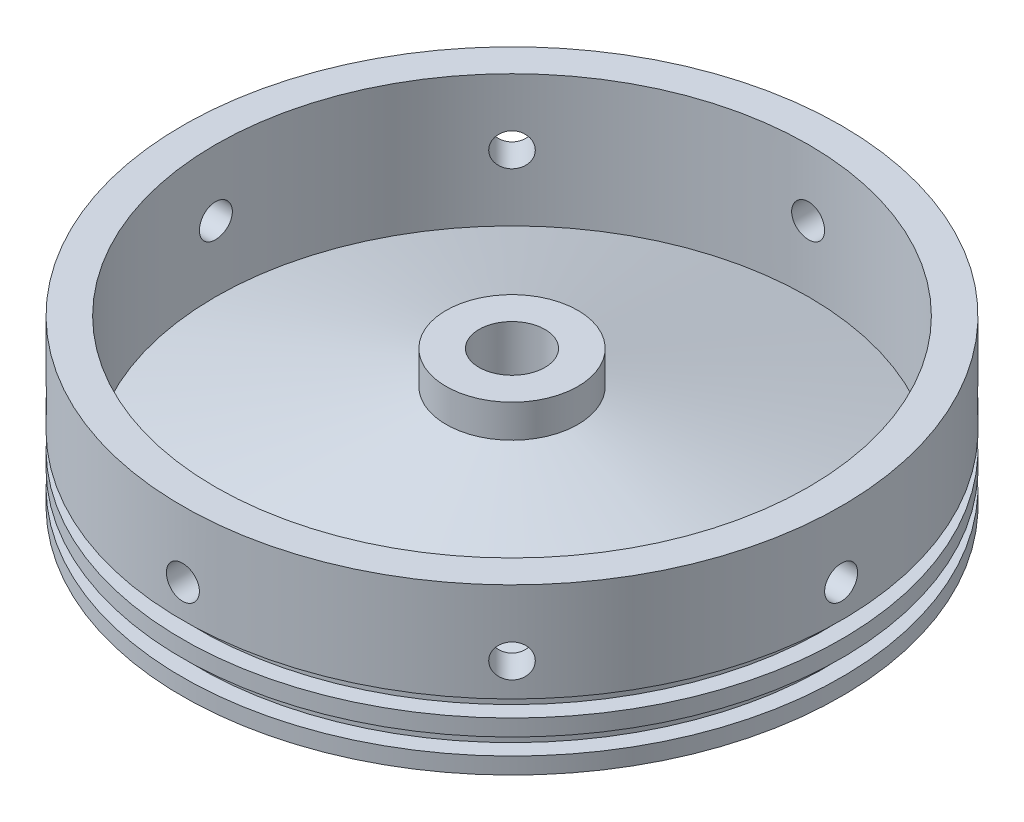
SolidWorks part; units mm, degrees
ref_plane "Front Plane" through (0, 0, 0) normal (0, 0, 1) x (1, 0, 0)
ref_plane "Top Plane" through (0, 0, 0) normal (0, 1, 0) x (1, 0, 0)
ref_plane "Right Plane" through (0, 0, 0) normal (1, 0, 0) x (0, 0, -1)
sketch "Sketch1" plane through (0, 0, 0) normal (0, 0, 1) x (1, 0, 0)
  line L2 (6.35, 32.6634) -> (6.35, 45.3634)
  line L11 (57.15, 50.8) -> (63.5, 50.8)
  line L13 (6.35, 45.3634) -> (12.7, 45.3634)
  line L14 (12.7, 45.3634) -> (12.7, 39.0134)
  line L15 (57.15, 50.8) -> (57.15, 25.4)
  line L16 (57.15, 25.4) -> (12.7, 39.0134)
  line L19 (0, 0) -> (0, 69.8674) construction
  line L21 (63.5, 50.8) -> (63.5, 19.05)
  line L23 (50.8, 19.05) -> (63.5, 19.05)
  line L24 (63.5, 22.225) -> (60.325, 22.225)
  line L25 (60.325, 22.225) -> (60.325, 25.4)
  line L26 (60.325, 25.4) -> (63.5, 25.4)
  line L27 (63.5, 28.575) -> (60.325, 28.575)
  line L28 (60.325, 28.575) -> (60.325, 31.75)
  line L29 (60.325, 31.75) -> (63.5, 31.75)
  arc A5 (50.8, 19.05) -> (6.35, 32.6634) centre (50.8, 98.425) cw
  point P2 (9.525, 45.3634)
  dimension "D4" = 50.8
  dimension "D9" = 79.375
  dimension "D2" = 63.5
  dimension "D3" = 6.35
  dimension "D5" = 6.35
  dimension "D6" = 12.7
  dimension "D7" = 12.7
  dimension "D8" = 6.35
  dimension "D10" = 45.3634
  dimension "D11" = 6.35
  dimension "D12" = 6.35
  dimension "D13" = 3.175
  dimension "D14" = 3.175
  dimension "D15" = 3.175
  dimension "D16" = 3.175
revolve "Revolve2" add sketch "Sketch1" angle 360 about L19
ref_plane "Plane1" through (0, 0, 63.5) normal (0, 0, 1) x (1, 0, 0)
sketch "Sketch3" plane through (0, 0, 63.5) normal (0, 0, 1) x (1, 0, 0)
  line L0 (0, 38.1) -> (0, 50.8) construction
  line L1 (63.5, 50.8) -> (-63.5, 50.8) construction
  circle A0 centre (0, 38.1) radius 3.175
  dimension "D1" = 6.35
  dimension "D2" = 12.7
extrude "Cut-Extrude2" cut sketch "Sketch3" against normal up to next
pattern_circular "CirPattern2" count 8 over 360 about axis through (0, 0, 0) along (0, -1, 0) of "Cut-Extrude2"
